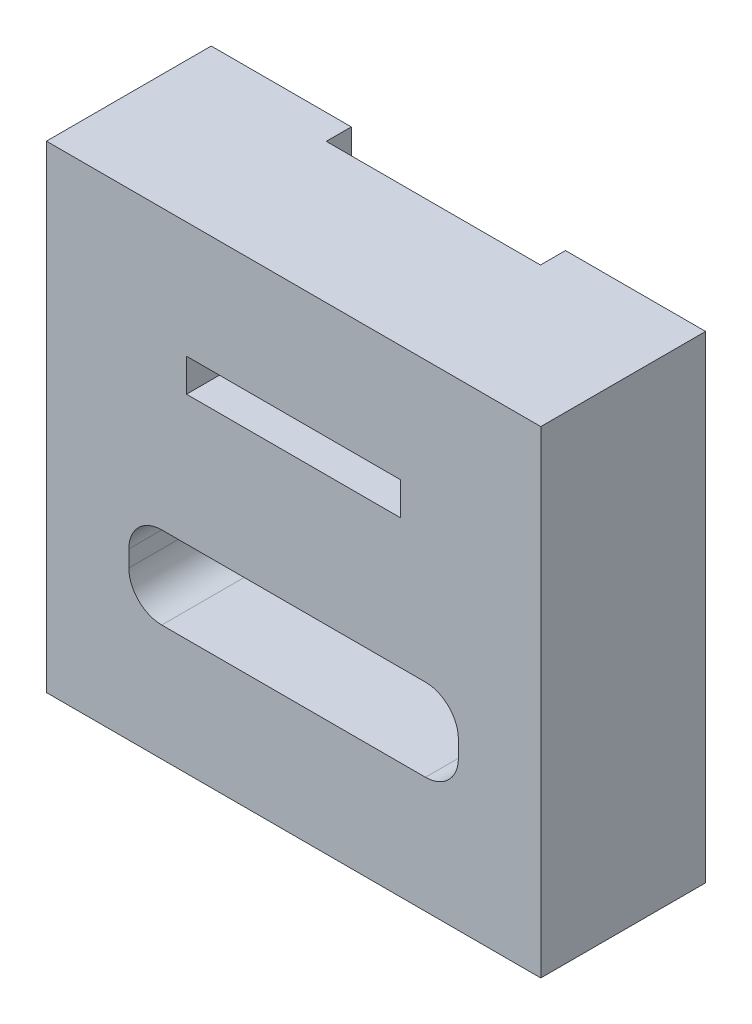
SolidWorks part; units mm, degrees
ref_plane "Front Plane" through (0, 0, 0) normal (0, 0, 1) x (1, 0, 0)
ref_plane "Top Plane" through (0, 0, 0) normal (0, 1, 0) x (1, 0, 0)
ref_plane "Right Plane" through (0, 0, 0) normal (1, 0, 0) x (0, 0, -1)
sketch "Sketch1" plane through (0, 0, 0) normal (0, 0, 1) x (1, 0, 0)
  line L0 (-4.7, -79.12) -> (11.3, -79.12) construction
  line L2 (11.3, -94) -> (-4.7, -94) construction
  line L3 (-3.2, -79.12) -> (9.8, -79.12)
  line L8 (-11.7, -72.07) -> (18.3, -72.07)
  line L9 (-11.7, -72.07) -> (-11.7, -101.05)
  line L10 (-11.7, -101.05) -> (18.3, -101.05)
  line L11 (18.3, -72.07) -> (18.3, -101.05)
  line L12 (-11.7, -72.07) -> (18.3, -101.05) construction
  line L13 (-11.7, -101.05) -> (18.3, -72.07) construction
  line L14 (9.8, -79.12) -> (9.8, -81.12)
  line L15 (9.8, -81.12) -> (-3.2, -81.12)
  line L16 (-3.2, -81.12) -> (-3.2, -79.12)
  line L21 (26.9, -101.05) -> (-7.7, -101.05) construction
  line L22 (-6.7, -92) -> (-6.7, -81.12) construction
  line L24 (13.3, -94) -> (-6.7, -94)
  line L25 (13.3, -94) -> (13.3, -89)
  line L26 (13.3, -89) -> (-6.7, -89)
  line L27 (-6.7, -94) -> (-6.7, -89)
  line L28 (13.3, -94) -> (-6.7, -89) construction
  line L29 (13.3, -89) -> (-6.7, -94) construction
  point P0 (3.3, -97.775)
  point P1 (3.3, -75.85)
  point P2 (0, 0)
  point P5 (3.3, -79.12)
  point P6 (0, 0)
  point P7 (3.3, -81.12)
  point P12 (3.3, -91.5)
  point P14 (3.3, -86.56)
  point P35 (-6.7, -86.56)
  dimension "D1" = 3.775
  dimension "D2" = 5
  dimension "D3" = 30
  dimension "D4" = 13
  dimension "D5" = 2
  dimension "D6" = 3.78
  dimension "D7" = 20
extrude "Boss-Extrude1" add sketch "Sketch1" along normal blind 10
fillet "Fillet1" radius 2 4 edges at (13.3, -94, 5) (13.3, -89, 5) (-6.7, -89, 5) (-6.7, -94, 5)
sketch "Sketch2" plane through (0, 0, 0) normal (0, 0, -1) x (-1, 0, 0)
  line L0 (-18.3, -72.07) -> (11.7, -72.07) construction
  line L1 (-9.8, -79.12) -> (3.2, -79.12)
  line L2 (-9.8, -79.12) -> (-9.8, -72.07)
  line L3 (-9.8, -72.07) -> (3.2, -72.07)
  line L4 (3.2, -79.12) -> (3.2, -72.07)
  point P7 (3.2, -79.26)
extrude "Cut-Extrude1" cut sketch "Sketch2" against normal blind 1.52
fillet "Fillet2" radius 2 1 edges at (3.3, -79.12, 1.52)
